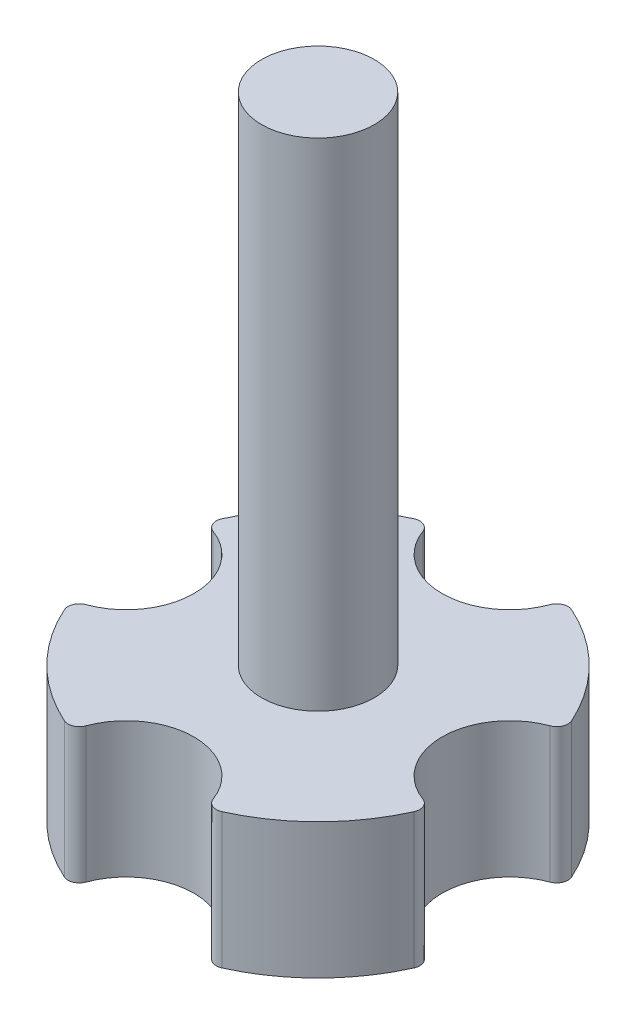
SolidWorks part; units mm, degrees
ref_plane "Front Plane" through (0, 0, 0) normal (0, 0, 1) x (1, 0, 0)
ref_plane "Top Plane" through (0, 0, 0) normal (0, 1, 0) x (1, 0, 0)
ref_plane "Right Plane" through (0, 0, 0) normal (1, 0, 0) x (0, 0, -1)
sketch "Sketch1" plane through (0, 0, 0) normal (0, 1, 0) x (1, 0, 0)
  circle A0 centre (0, 0) radius 8.5
  dimension "D1" = 17
extrude "Boss-Extrude1" add sketch "Sketch1" along normal blind 6
sketch "Sketch2" plane through (0, 6, 0) normal (0, 1, 0) x (1, 0, 0)
  circle A0 centre (0, 0) radius 2.5
  dimension "D1" = 5
extrude "Boss-Extrude2" add sketch "Sketch2" along normal blind 22
sketch "Sketch3" plane through (0, 6, 0) normal (0, 1, 0) x (1, 0, 0)
  circle A0 centre (-8.5, 0) radius 3
  circle A1 centre (0, 0) radius 8.5 construction
  circle A2 centre (0, 8.5) radius 3
  circle A3 centre (8.5, 0) radius 3
  circle A4 centre (0, -8.5) radius 3
  dimension "D1" = 6
  dimension "D2" = 6
  dimension "D3" = 6
  dimension "D4" = 6
extrude "Cut-Extrude1" cut sketch "Sketch3" against normal blind 13
fillet "Fillet1" radius 0.5 8 edges at (7.9706, 3, -2.9529) (7.9706, 3, 2.9529) (-2.9529, 3, -7.9706) (2.9529, 3, -7.9706) (-7.9706, 3, 2.9529) (-7.9706, 3, -2.9529) (2.9529, 3, 7.9706) (-2.9529, 3, 7.9706)
